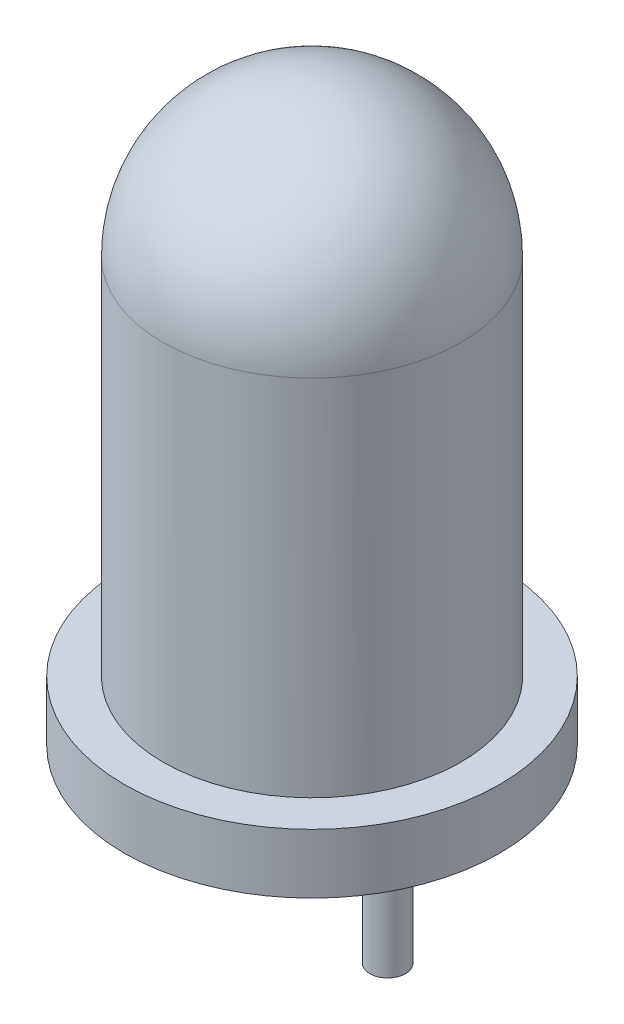
SolidWorks part; units mm, degrees
ref_plane "Front Plane" through (0, 0, 0) normal (0, 0, 1) x (1, 0, 0)
ref_plane "Top Plane" through (0, 0, 0) normal (0, 1, 0) x (1, 0, 0)
ref_plane "Right Plane" through (0, 0, 0) normal (1, 0, 0) x (0, 0, -1)
sketch "Sketch1" plane through (0, 0, 0) normal (0, 0, 1) x (1, 0, 0)
  line L0 (2.5, 7.1) -> (2.5, 1)
  line L1 (2.5, 1) -> (3.1489, 1)
  line L2 (3.1489, 1) -> (3.1489, 0)
  line L3 (3.1489, 0) -> (0, 0)
  line L4 (0, 7.1) -> (0, 0)
  line L5 (0, 7.1) -> (0, 9.6)
  arc A0 (2.5, 7.1) -> (0, 9.6) centre (0, 7.1) ccw
  dimension "D1" = 5
  dimension "D2" = 1
  dimension "D3" = 6.1
  dimension "D4" = 3.1489
  dimension "D5" = 0.6489
revolve "Revolve1" add sketch "Sketch1" angle 360 about L4
sketch "Sketch2" plane through (0, 0, 0) normal (0, -1, 0) x (1, 0, 0)
  line L0 (-3.1489, 0) -> (3.1489, 0) construction
  line L1 (0, 3.1489) -> (0, -3.1489) construction
  circle A0 centre (0, 0) radius 3.1489 construction
  circle A1 centre (-1.27, 0) radius 0.3
  circle A2 centre (1.27, 0) radius 0.3
  dimension "D1" = 0.6
  dimension "D2" = 1.27
extrude "Boss-Extrude1" add sketch "Sketch2" along normal blind 2.54
